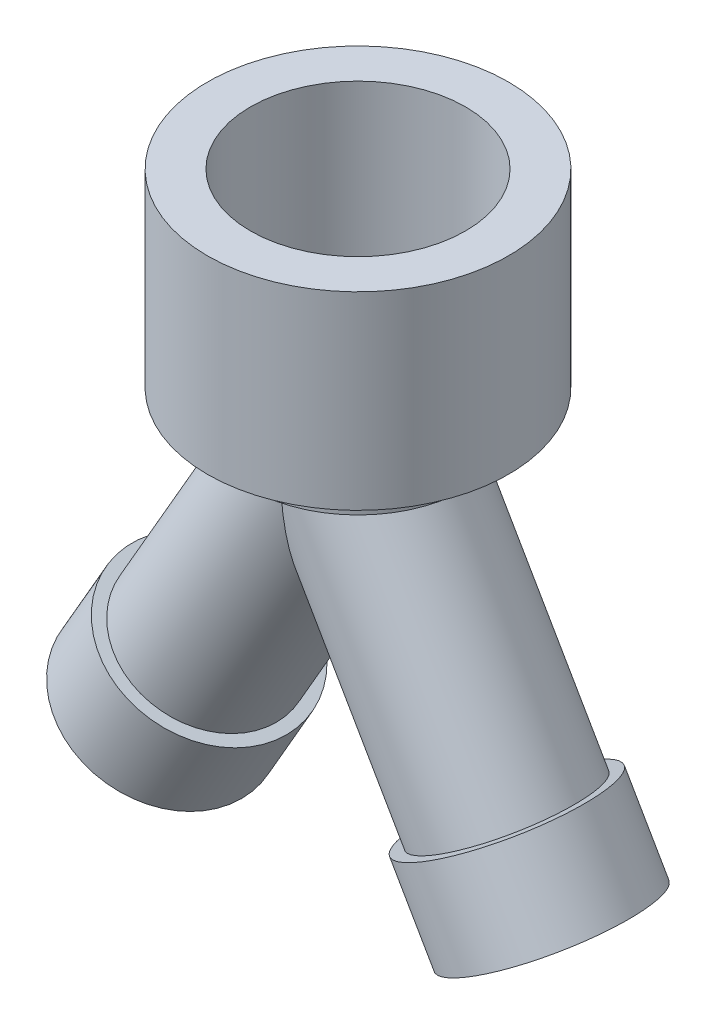
SolidWorks part; units mm, degrees
material "PVC Rigid"
ref_plane "Front" through (0, 0, 0) normal (0, 0, 1) x (1, 0, 0)
ref_plane "Top" through (0, 0, 0) normal (0, 1, 0) x (1, 0, 0)
ref_plane "Right" through (0, 0, 0) normal (1, 0, 0) x (0, 0, -1)
sketch "Sketch1" plane through (0, 0, 0) normal (0, 1, 0) x (1, 0, 0)
  circle A0 centre (0, 0) radius 22.225
  circle A1 centre (0, 0) radius 15.875
  dimension "D1" = 44.45
  dimension "D2" = 31.75
extrude "Boss-Extrude1" add sketch "Sketch1" along normal blind 25.4
sketch "Sketch2" plane through (0, 0, 0) normal (0, -1, 0) x (1, 0, 0)
  circle A0 centre (0, 0) radius 22.225
  circle A1 centre (0, 0) radius 22.225 construction
extrude "Boss-Extrude2" add sketch "Sketch2" along normal blind 2.54
sketch "Sketch3" plane through (0, -2.54, 0) normal (0, -1, 0) x (1, 0, 0)
  circle A0 centre (0, 0) radius 15.875
  dimension "D1" = 31.75
extrude "Boss-Extrude3" add sketch "Sketch3" along normal blind 5.08
sketch "Sketch4" plane through (0, 0, 0) normal (0, 0, 1) x (1, 0, 0)
  line L0 (0, -7.62) -> (-28.575, -57.1134) construction
  line L1 (-15.875, -7.62) -> (15.875, -7.62) construction
  line L2 (0, 0) -> (0, -7.62) construction
  line L3 (-28.575, -57.1134) -> (-38.4737, -51.3984) construction
  line L4 (-38.4737, -51.3984) -> (-9.8987, -1.905)
  line L5 (-9.8987, -1.905) -> (0, -7.62) construction
  line L7 (-9.8987, -1.905) -> (-6.5991, -3.81)
  line L8 (-6.5991, -3.81) -> (-35.1741, -53.3034)
  line L9 (-35.1741, -53.3034) -> (-38.4737, -51.3984)
  dimension "D1" = 30
  dimension "D2" = 57.15
  dimension "D3" = 22.86
  dimension "D4" = 3.81
revolve "Revolve1" add sketch "Sketch4" angle 360 about L0
sketch "Sketch5" plane through (-31.8746, -55.2084, 0) normal (-0.5, -0.866, 0) x (0.866, -0.5, 0)
  circle A0 centre (3.81, 0) radius 13.1514
  circle A3 centre (3.81, 0) radius 11.43 construction
  circle A4 centre (3.81, 0) radius 11.43
  dimension "D1" = 26.3028
extrude "Boss-Extrude4" add sketch "Sketch5" against normal blind 13.208
mirror "Mirror1" about plane through (0, 0, 0) normal (1, 0, 0) of "Boss-Extrude4", "Revolve1"
